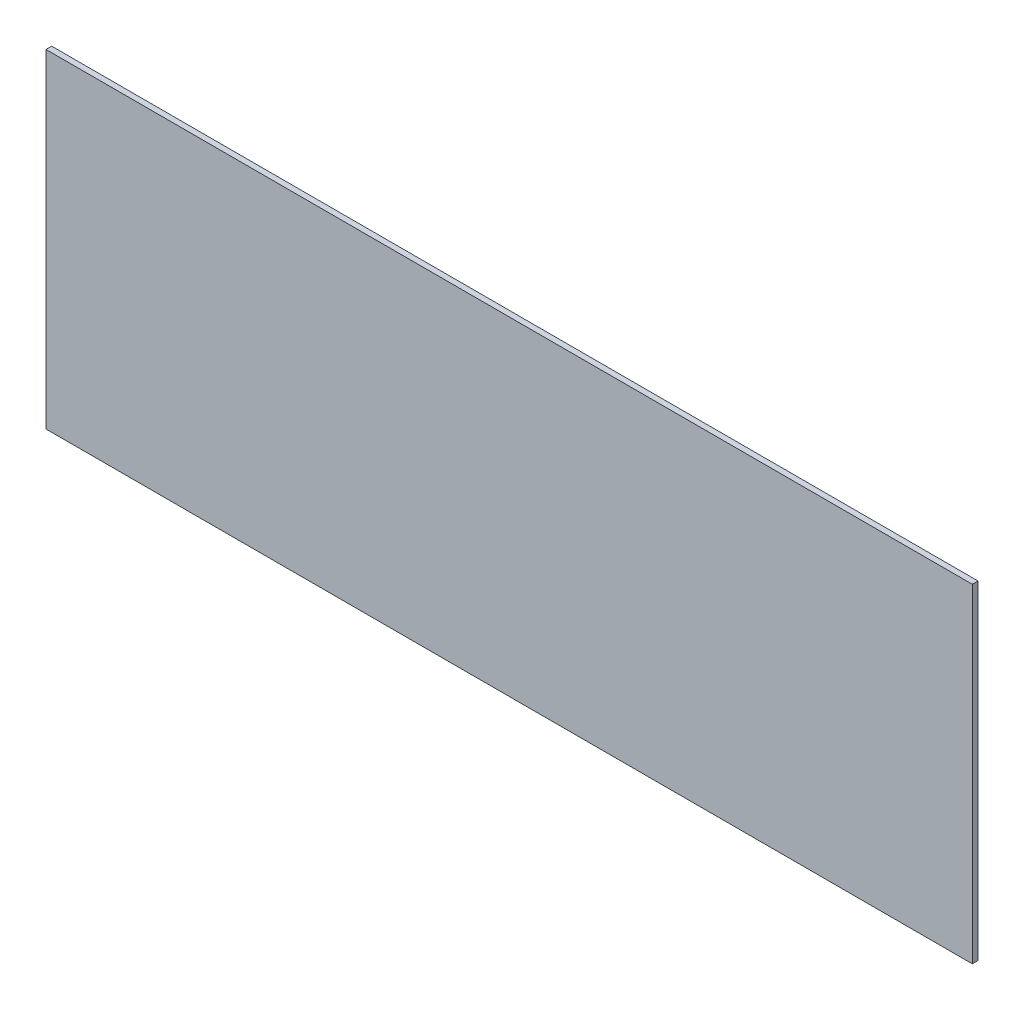
SolidWorks part; units mm, degrees
ref_plane "Front Plane" through (0, 0, 0) normal (0, 0, 1) x (1, 0, 0)
ref_plane "Top Plane" through (0, 0, 0) normal (0, 1, 0) x (1, 0, 0)
ref_plane "Right Plane" through (0, 0, 0) normal (1, 0, 0) x (0, 0, -1)
sketch "Sketch1" plane through (0, 0, 0) normal (0, 0, 1) x (1, 0, 0)
  line L0 (0, 0) -> (0, 57.5)
  line L1 (0, 57.5) -> (162.024, 57.5)
  line L2 (162.024, 57.5) -> (162.024, 0)
  line L3 (162.024, 0) -> (0, 0)
  dimension "D1" = 57.5
  dimension "D2" = 162.024
extrude "Boss-Extrude1" add sketch "Sketch1" along normal blind 1
